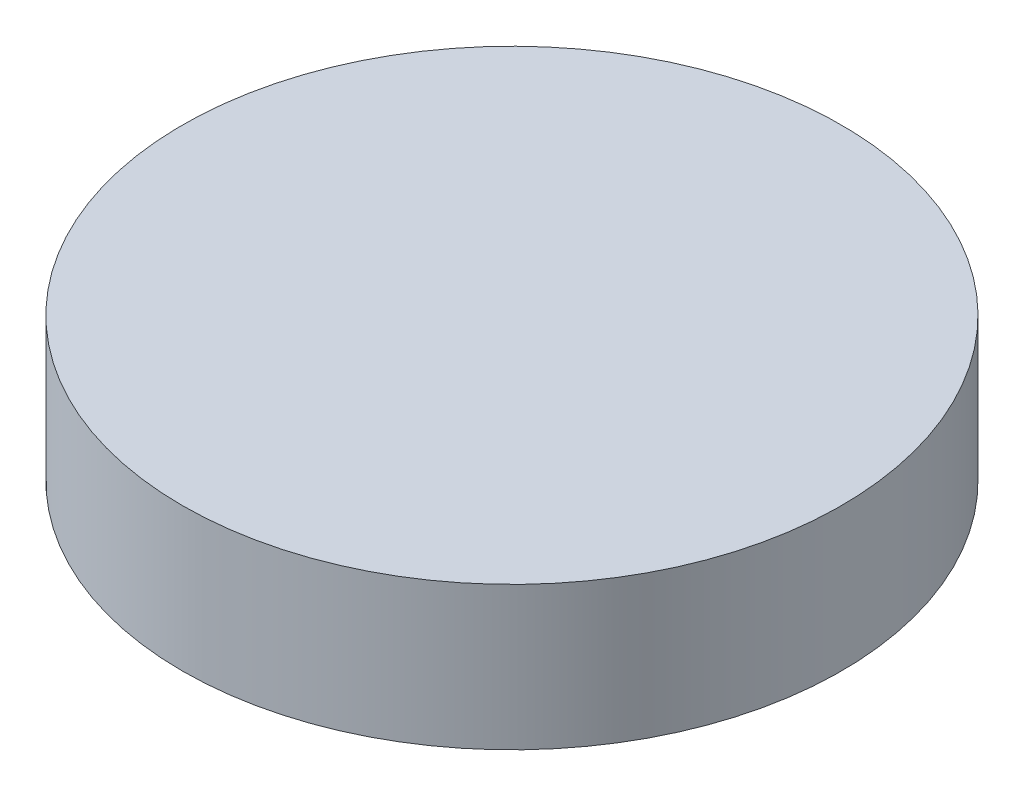
SolidWorks part; units mm, degrees
ref_plane "Alzado" through (0, 0, 0) normal (0, 0, 1) x (1, 0, 0)
ref_plane "Planta" through (0, 0, 0) normal (0, 1, 0) x (1, 0, 0)
ref_plane "Vista lateral" through (0, 0, 0) normal (1, 0, 0) x (0, 0, -1)
sketch "Croquis2" plane through (0, 0, 0) normal (0, 0, 1) x (1, 0, 0)
  line L0 (-91.414, -2.7248) -> (-92.914, -2.7248)
  line L1 (-92.914, -2.7248) -> (-92.914, 4.7752)
  line L2 (-92.914, 4.7752) -> (-75.664, 4.7752)
  line L3 (-75.664, 4.7752) -> (-75.664, 3.2752)
  line L4 (-75.664, 3.2752) -> (-91.414, 3.2752)
  line L5 (-91.414, 3.2752) -> (-91.414, -2.7248)
  dimension "D1" = 1.5
  dimension "D2" = 7.5
  dimension "D3" = 17.25
  dimension "D4" = 1.5
revolve "Revolución1" add sketch "Croquis2" angle 360 about L3
